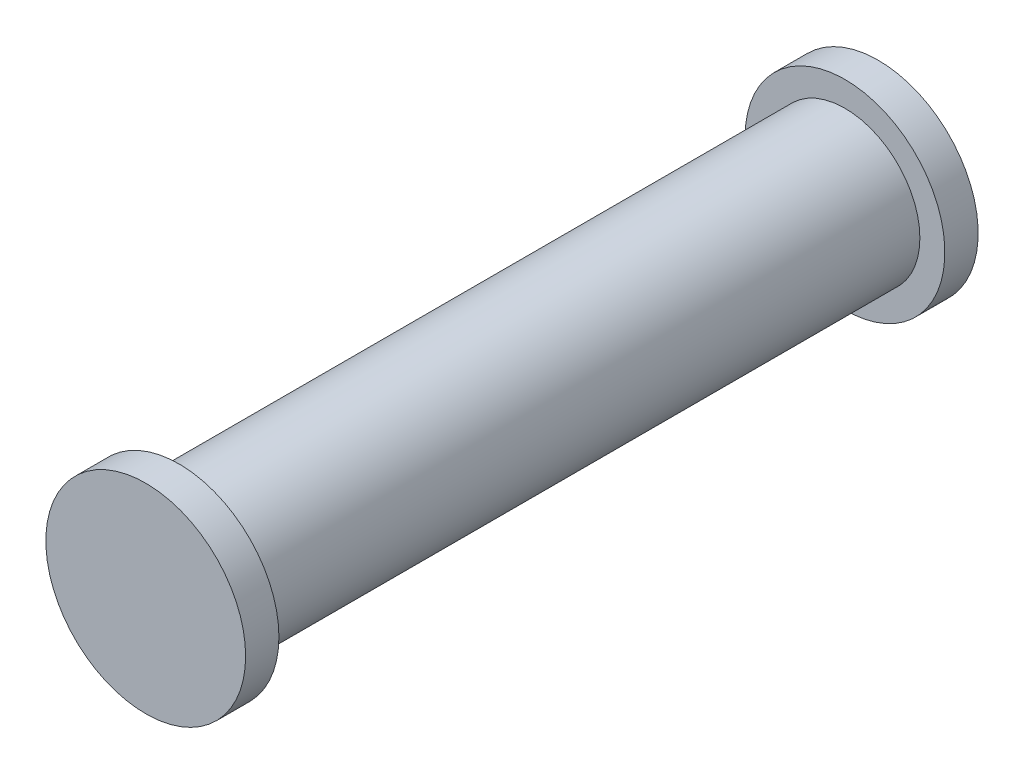
SolidWorks part; units mm, degrees
ref_plane "Ebene vorne" through (0, 0, 0) normal (0, 0, 1) x (1, 0, 0)
ref_plane "Ebene oben" through (0, 0, 0) normal (0, 1, 0) x (1, 0, 0)
ref_plane "Ebene rechts" through (0, 0, 0) normal (1, 0, 0) x (0, 0, -1)
sketch "Skizze1" plane through (0, 0, 0) normal (0, 0, 1) x (1, 0, 0)
  circle A0 centre (-14.9, 15.1) radius 2.25
  dimension "D1" = 4.5
extrude "Aufsatz-Linear austragen1" add sketch "Skizze1" against normal up to surface (20 mm away)
sketch "Skizze2" plane through (0, 0, 0) normal (0, 0, 1) x (1, 0, 0)
  circle A0 centre (-14.9, 15.1) radius 3
  dimension "D1" = 6
extrude "Aufsatz-Linear austragen2" add sketch "Skizze2" along normal blind 1
sketch "Skizze3" plane through (0, 0, -20) normal (0, 0, -1) x (-1, 0, 0)
  circle A0 centre (14.9, 15.1) radius 3
  dimension "D1" = 6
extrude "Aufsatz-Linear austragen3" add sketch "Skizze3" along normal blind 1
